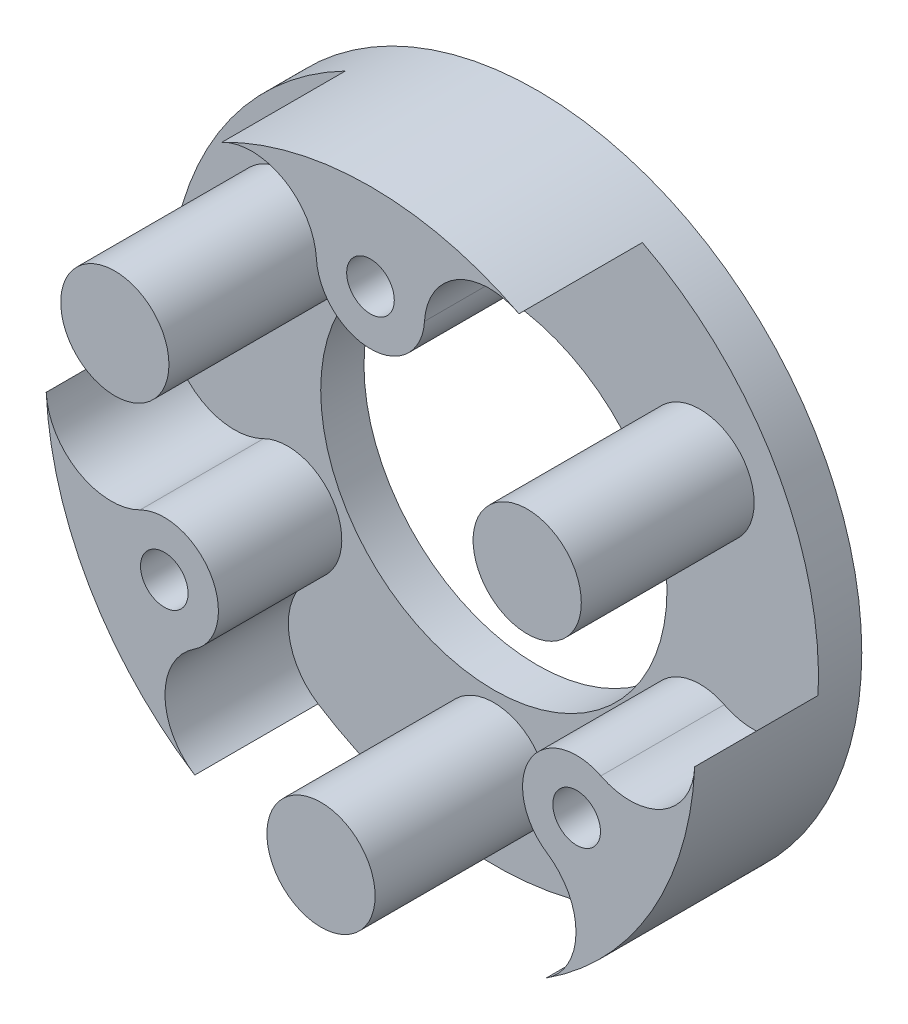
SolidWorks part; units mm, degrees
ref_plane "Front Plane" through (0, 0, 0) normal (0, 0, 1) x (1, 0, 0)
ref_plane "Top Plane" through (0, 0, 0) normal (0, 1, 0) x (1, 0, 0)
ref_plane "Right Plane" through (0, 0, 0) normal (1, 0, 0) x (0, 0, -1)
sketch "Sketch1" plane through (0, 0, 0) normal (0, 0, 1) x (1, 0, 0)
  line L0 (0, 0) -> (12.9904, 7.5) construction
  line L1 (0, 0) -> (0, 15) construction
  circle A0 centre (0, 0) radius 8
  circle A1 centre (0, 0) radius 15
  circle A2 centre (9.5263, 5.5) radius 1.5
  circle A3 centre (0, -11) radius 1.5
  circle A4 centre (-9.5263, 5.5) radius 1.5
  point P14 (0, 0)
  dimension "D1" = 16
  dimension "D2" = 30
  dimension "D4" = 3
  dimension "D3" = 60
  dimension "D5" = 11
  dimension "D6" = 3
extrude "Boss-Extrude1" add sketch "Sketch1" along normal blind 2
sketch "Sketch2" plane through (0, 0, 2) normal (0, 0, 1) x (1, 0, 0)
  circle A0 centre (0, 0) radius 8 construction
  circle A1 centre (0, 0) radius 15 construction
  circle A2 centre (0, -11) radius 1.5 construction
  circle A3 centre (-9.5263, 5.5) radius 1.5 construction
  circle A4 centre (9.5263, 5.5) radius 1.5 construction
  circle A5 centre (0, 0) radius 8
  circle A6 centre (0, 0) radius 15
  circle A7 centre (0, -11) radius 1.5
  circle A8 centre (-9.5263, 5.5) radius 1.5
  circle A9 centre (9.5263, 5.5) radius 1.5
  circle A10 centre (9.5263, 5.5) radius 2.5
  circle A11 centre (-9.5263, 5.5) radius 2.5
  circle A12 centre (0, -11) radius 2.5
  circle M7 centre (0, -11) radius 1.5
  circle M10 centre (9.5263, 5.5) radius 1.5
  circle M11 centre (-9.5263, 5.5) radius 1.5
  dimension "D1" = 5
extrude "Boss-Extrude2" add sketch "Sketch2" along normal blind 7.9856 contours A11 M11 | A10 M10 | M11 | M10 | A12 M7 | M7
sketch "Sketch3" plane through (0, 0, 2) normal (0, 0, 1) x (1, 0, 0)
  line L0 (0, 0) -> (0, 15) construction
  circle A0 centre (0, 0) radius 8 construction
  circle A1 centre (0, 0) radius 15 construction
  circle A2 centre (0, 0) radius 8
  circle A3 centre (0, 0) radius 15
  circle A4 centre (0, -11) radius 2.5 construction
  circle A5 centre (9.5263, 5.5) radius 2.5 construction
  circle A6 centre (-9.5263, 5.5) radius 2.5 construction
  circle A7 centre (0, -11) radius 2.5
  circle A8 centre (9.5263, 5.5) radius 2.5
  circle A9 centre (-9.5263, 5.5) radius 2.5
  arc A10 (-2.4955, 10.8502) -> (2.4955, 10.8502) centre (0, 11) ccw
  arc A11 (2.4955, 10.8502) -> (6.8626, 13.3381) centre (5.4901, 10.6705) cw
  arc A12 (-2.4955, 10.8502) -> (-6.8626, 13.3381) centre (-5.4901, 10.6705) ccw
  circle A13 centre (0, 11) radius 1.1
  arc A14 (8.1488, -7.5863) -> (8.1198, -12.6123) centre (6.4958, -10.0898) cw
  arc A15 (10.6443, -3.2639) -> (8.1488, -7.5863) centre (9.5263, -5.5) ccw
  circle A16 centre (9.5263, -5.5) radius 1.1
  arc A17 (10.6443, -3.2639) -> (14.9824, -0.7258) centre (11.9859, -0.5806) ccw
  arc A18 (-10.6443, -3.2639) -> (-14.9824, -0.7258) centre (-11.9859, -0.5806) cw
  arc A19 (-8.1488, -7.5863) -> (-10.6443, -3.2639) centre (-9.5263, -5.5) ccw
  circle A20 centre (-9.5263, -5.5) radius 1.1
  arc A21 (-8.1488, -7.5863) -> (-8.1198, -12.6123) centre (-6.4958, -10.0898) ccw
  point P17 (0, 8)
  point P42 (0, 0)
  circle M9 centre (0, 0) radius 15
  dimension "D2" = 5
  dimension "D3" = 3
  dimension "D5" = 2.2
  dimension "D6" = 3
  dimension "D1" = 11
extrude "Boss-Extrude3" add sketch "Sketch3" along normal blind 5.7 contours A21 A19 A18 A20 M9 | A17 A15 A14 A16 M9 | A10 L0 A13 A3 A12 | L0 A10 A11 A13 M9
